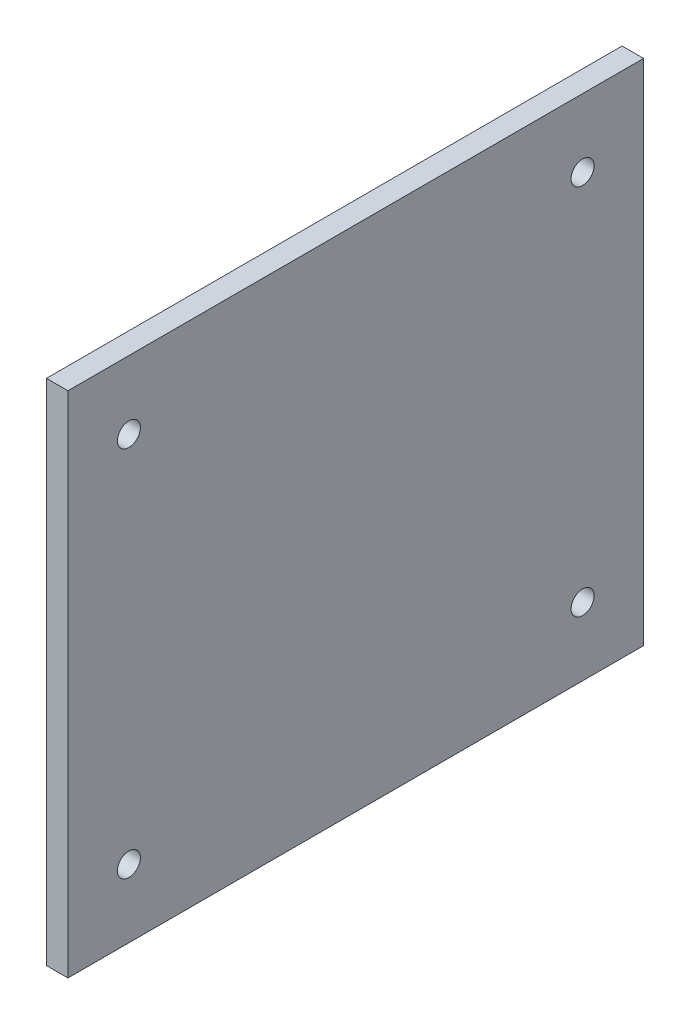
SolidWorks part; units mm, degrees
ref_plane "Front Plane" through (0, 0, 0) normal (0, 0, 1) x (1, 0, 0)
ref_plane "Top Plane" through (0, 0, 0) normal (0, 1, 0) x (1, 0, 0)
ref_plane "Right Plane" through (0, 0, 0) normal (1, 0, 0) x (0, 0, -1)
sketch "Sketch1" plane through (0, 0, 0) normal (1, 0, 0) x (0, 0, -1)
  line L0 (0, 37.55) -> (85, 37.55) construction
  line L1 (0, 0) -> (85, 0)
  line L2 (0, 0) -> (0, 75.1)
  line L3 (0, 75.1) -> (85, 75.1)
  line L4 (85, 0) -> (85, 75.1)
  line L5 (42.5, 75.1) -> (42.5, 0) construction
  circle A0 centre (9, 65.05) radius 1.7
  circle A1 centre (9, 10.05) radius 1.7
  circle A2 centre (76, 10.05) radius 1.7
  circle A3 centre (76, 65.05) radius 1.7
  dimension "D5" = 3.4
  dimension "D1" = 75.1
  dimension "D2" = 85
  dimension "D3" = 10.05
  dimension "D4" = 9
extrude "Boss-Extrude1" add sketch "Sketch1" along normal blind 3.175
